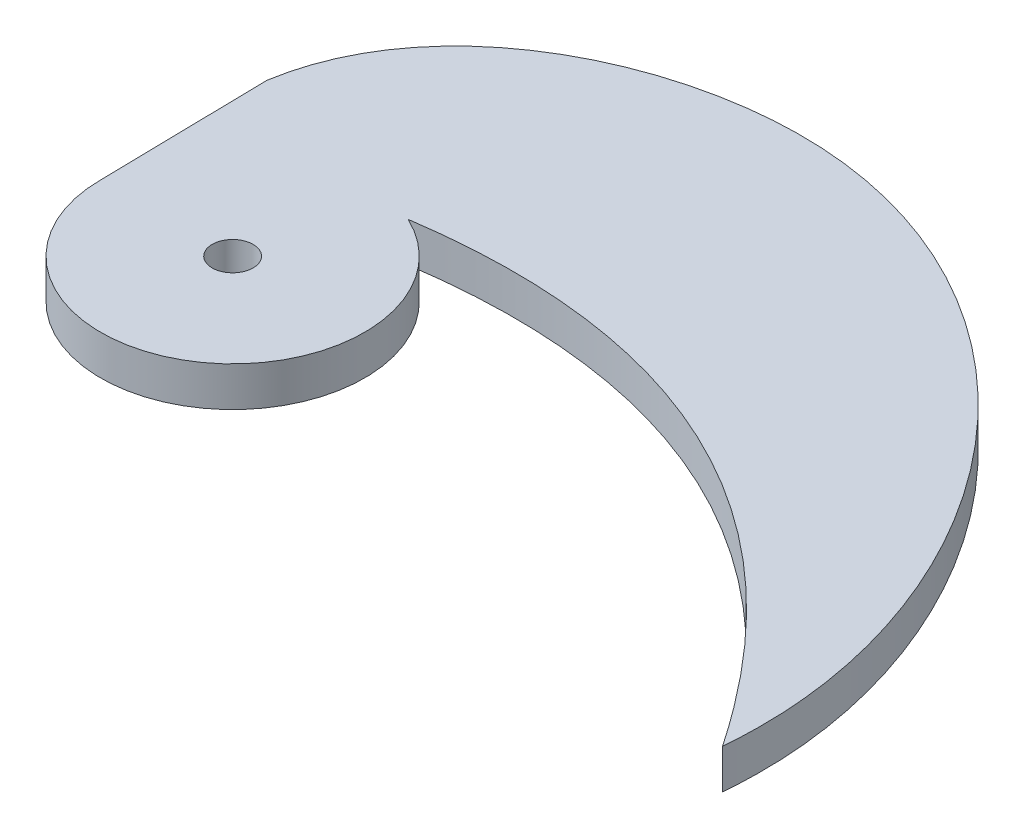
SolidWorks part; units mm, degrees
ref_plane "Front Plane" through (0, 0, 0) normal (0, 0, 1) x (1, 0, 0)
ref_plane "Top Plane" through (0, 0, 0) normal (0, 1, 0) x (1, 0, 0)
ref_plane "Right Plane" through (0, 0, 0) normal (1, 0, 0) x (0, 0, -1)
sketch "Sketch1" plane through (0, 0, 0) normal (0, 1, 0) x (1, 0, 0)
  line L0 (0, 0) -> (-0.8023, 2.9944)
  line L1 (0, 0) -> (1.3101, 2.8096)
  line L2 (0, 0) -> (2.8096, 1.3101)
  line L3 (0, 0) -> (2.9944, -0.8023)
  line L5 (0, 0) -> (-2.5394, 1.7781)
  line L6 (-20.4788, 25.6588) -> (-20, 0)
  circle A0 centre (0, 0) radius 3.1
  arc A1 (-20, 0) -> (8.4524, 18.1262) centre (0, 0) ccw
  spline S0 degree 3 poles (-20.4788, 25.6588) (-19.3693, 32.6401) (-9.5558, 50.9887) (57.2952, 74.5844) (105.0946, 12.8549) (101.4222, -27.176) knots 0.052355 0.052355 0.052355 0.052355 0.156266 0.372181 1 1 1 1
  spline S1 degree 2 poles (8.4524, 18.1262) (65.0149, 26.5132) (101.4222, -27.176) knots 0 0 0 1 1 1
extrude "Boss-Extrude1" add sketch "Sketch1" along normal blind 6 contours A1 S1 S0 L6 A0
